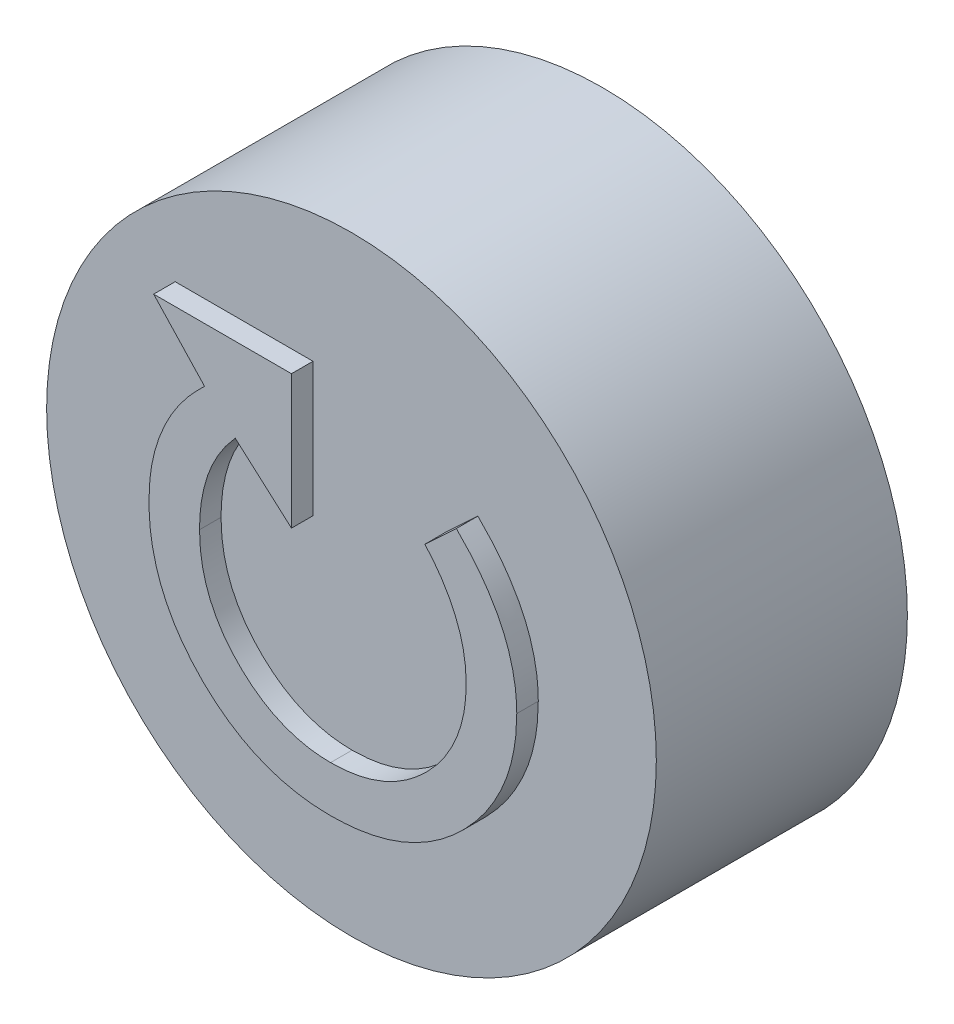
SolidWorks part; units mm, degrees
ref_plane "Front Plane" through (0, 0, 0) normal (0, 0, 1) x (1, 0, 0)
ref_plane "Top Plane" through (0, 0, 0) normal (0, 1, 0) x (1, 0, 0)
ref_plane "Right Plane" through (0, 0, 0) normal (1, 0, 0) x (0, 0, -1)
sketch "Sketch1" plane through (0, 0, 0) normal (0, 0, 1) x (1, 0, 0)
  circle A0 centre (0, 0) radius 8.5
  dimension "D1" = 17
extrude "Boss-Extrude1" add sketch "Sketch1" along normal blind 7
sketch "Sketch2" plane through (0, 0, 7) normal (0, 0, 1) x (1, 0, 0)
  line L13 (-6.981, -5.2749) -> (6.8865, -5.2749) construction
  text T1 "<b>P</b>" font "Wingdings 3" height 10
  point P0 (-6.981, -5.2749)
  point P3 (-6.0095, -3.579)
  point P4 (6.8865, -3.318)
  point P5 (-7.5685, -3.3198)
extrude "Boss-Extrude2" add sketch "Sketch2" along normal blind 0.6
sketch "Sketch3" plane through (0, 0, 0) normal (0, 0, -1) x (-1, 0, 0)
  circle A0 centre (0, 0) radius 5.8
  dimension "D1" = 11.6
extrude "Cut-Extrude1" cut sketch "Sketch3" against normal blind 4.15
